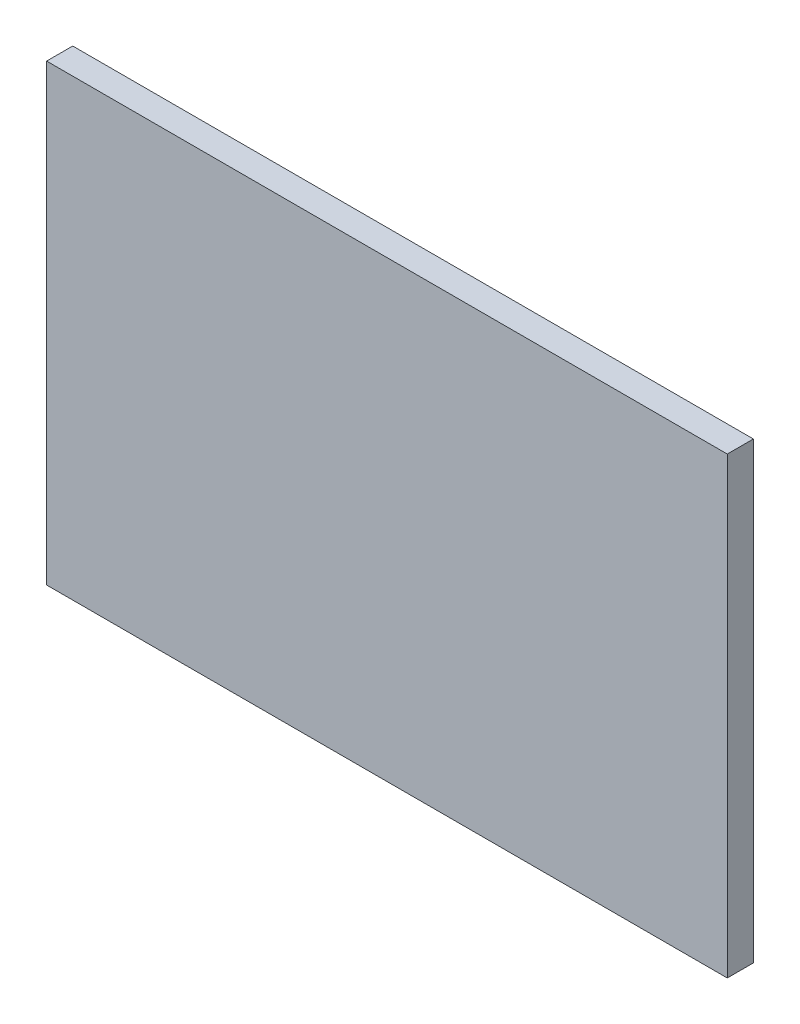
SolidWorks part; units mm, degrees
material "ABS PC"
ref_plane "Front Plane" through (0, 0, 0) normal (0, 0, 1) x (1, 0, 0)
ref_plane "Top Plane" through (0, 0, 0) normal (0, 1, 0) x (1, 0, 0)
ref_plane "Right Plane" through (0, 0, 0) normal (1, 0, 0) x (0, 0, -1)
sketch "Sketch1" plane through (0, 0, 0) normal (0, 0, 1) x (1, 0, 0)
  line L1 (0, 50.8) -> (76.2, 50.8)
  line L2 (0, 50.8) -> (0, 0)
  line L3 (0, 0) -> (76.2, 0)
  line L4 (76.2, 50.8) -> (76.2, 0)
  dimension "D1" = 76.2
  dimension "D2" = 50.8
extrude "Boss-Extrude1" add sketch "Sketch1" against normal blind 2.921
